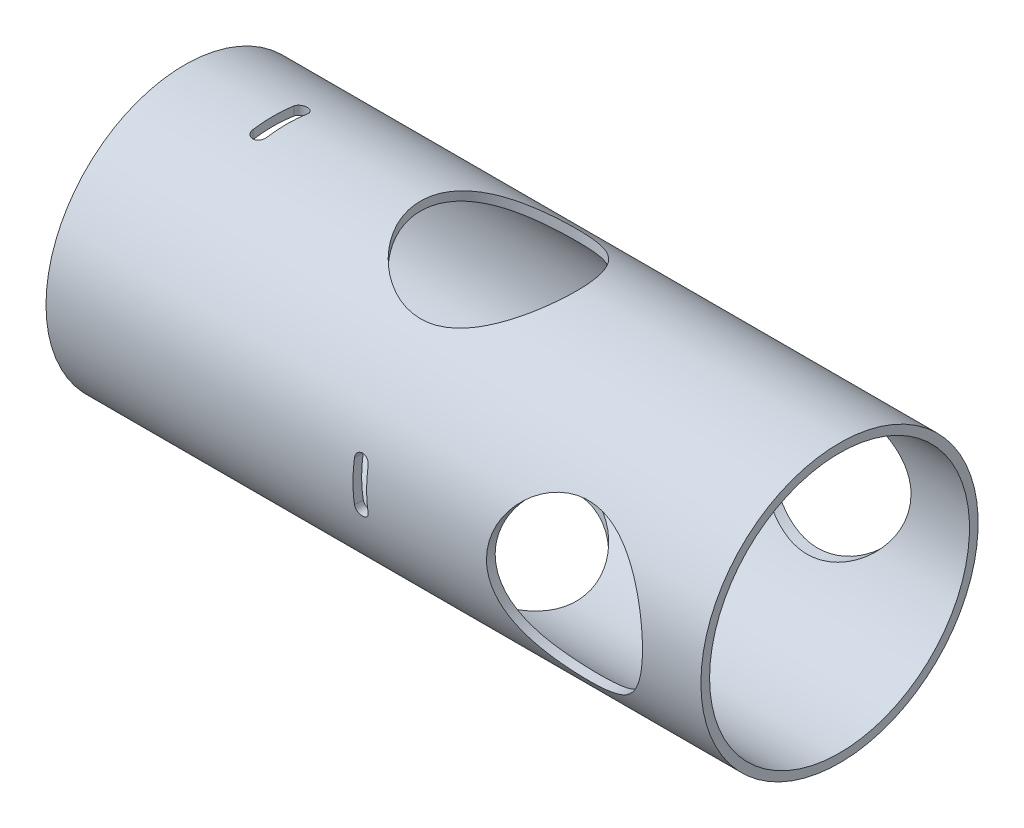
SolidWorks part; units mm, degrees
ref_plane "Front Plane" through (0, 0, 0) normal (0, 0, 1) x (1, 0, 0)
ref_plane "Top Plane" through (0, 0, 0) normal (0, 1, 0) x (1, 0, 0)
ref_plane "Right Plane" through (0, 0, 0) normal (1, 0, 0) x (0, 0, -1)
sketch "Sketch1" plane through (0, 0, 0) normal (0, 1, 0) x (1, 0, 0)
  line L0 (0, 101.6) -> (480, 101.6)
  line L1 (0, -111.265) -> (0, 111.265) construction
  line L2 (0, 95.25) -> (480, 95.25)
  line L4 (480, 95.25) -> (480, 101.6)
  line L7 (0, 95.25) -> (0, 101.6)
  line L8 (78.3131, 0) -> (302.645, 0) construction
  dimension "D1" = 6.35
  dimension "D2" = 101.6
  dimension "D4" = 480
revolve "Revolve1" add sketch "Sketch1" angle 360 about L8
sketch "Sketch2" plane through (0, 0, 0) normal (0, 0, 1) x (1, 0, 0)
  line L1 (480, -101.6) -> (480, 101.6) construction
  circle A0 centre (380, 0) radius 57.15
  dimension "D1" = 114.3
  dimension "D2" = 100
extrude "Cut-Extrude1" cut sketch "Sketch2" against normal through all and the other way through all
sketch "Sketch3" plane through (0, 0, 0) normal (0, 1, 0) x (1, 0, 0)
  line L1 (480, -95.25) -> (480, 95.25) construction
  circle A0 centre (230, 0) radius 57.15
  dimension "D1" = 114.3
  dimension "D2" = 250
extrude "Cut-Extrude2" cut sketch "Sketch3" against normal through all and the other way through all
sketch "Sketch4" plane through (0, 0, 0) normal (0, 0, 1) x (1, 0, 0)
  line L1 (111.265, 0) -> (-111.265, 0) construction
  line L2 (480, -101.6) -> (480, 101.6) construction
  line L3 (225, 15) -> (225, -15)
  line L4 (235, 15) -> (235, -15)
  arc A0 (235, 15) -> (225, 15) centre (230, 15) ccw
  arc A1 (225, -15) -> (235, -15) centre (230, -15) ccw
  dimension "D1" = 10
  dimension "D2" = 10
  dimension "D3" = 30
  dimension "D4" = 15
  dimension "D5" = 250
  dimension "D6" = 250
extrude "Cut-Extrude3" cut sketch "Sketch4" against normal through all and the other way through all
sketch "Sketch5" plane through (0, 0, 0) normal (0, 1, 0) x (1, 0, 0)
  line L0 (0, -111.265) -> (0, 111.265) construction
  line L1 (-111.265, 0) -> (111.265, 0) construction
  line L2 (65, -15) -> (65, 15)
  line L3 (75, -15) -> (75, 15)
  arc A0 (65, -15) -> (75, -15) centre (70, -15) ccw
  arc A1 (75, 15) -> (65, 15) centre (70, 15) ccw
  dimension "D1" = 70
  dimension "D2" = 70
  dimension "D3" = 10
  dimension "D4" = 15
  dimension "D5" = 15
  dimension "D6" = 10
extrude "Cut-Extrude4" cut sketch "Sketch5" against normal through all both and the other way through all
